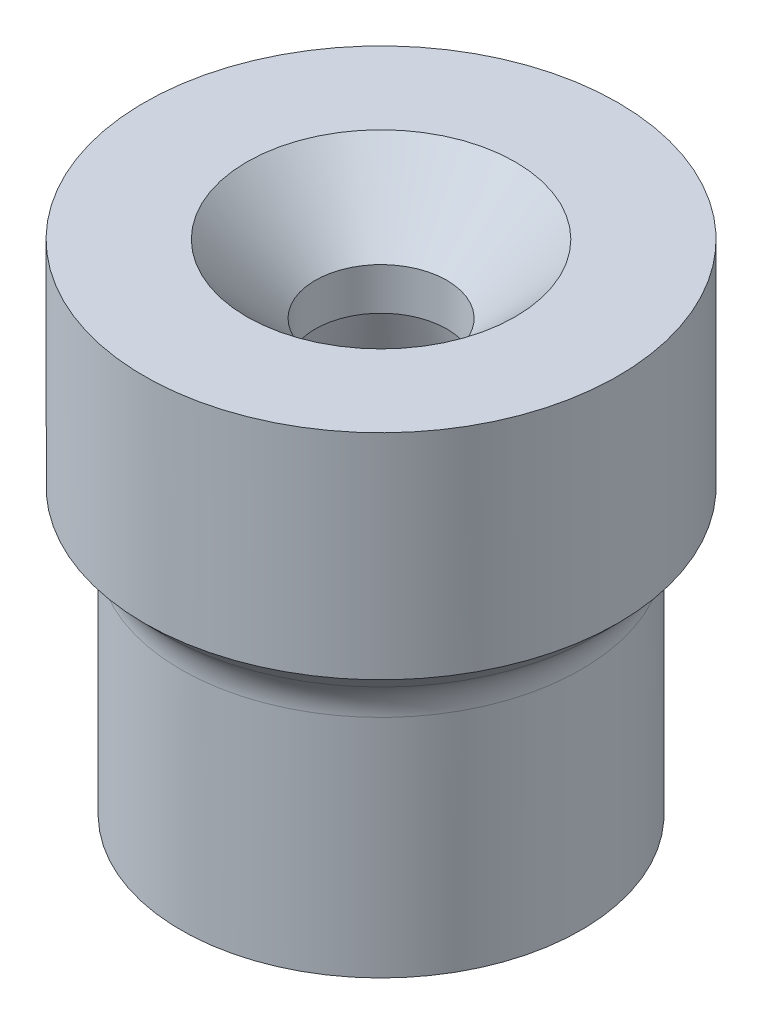
SolidWorks part; units mm, degrees
material "C (Grafite)"
ref_plane "Piano frontale" through (0, 0, 0) normal (0, 0, 1) x (1, 0, 0)
ref_plane "Piano superiore" through (0, 0, 0) normal (0, 1, 0) x (1, 0, 0)
ref_plane "Piano destro" through (0, 0, 0) normal (1, 0, 0) x (0, 0, -1)
sketch "Schizzo1" plane through (0, 0, 0) normal (0, 0, 1) x (1, 0, 0)
  line L0 (0, 0) -> (0, 63.7736) construction
  line L1 (-32.2345, 0) -> (-12.5, 73.6501)
  line L2 (-12.5, 73.6501) -> (-12.5, 81.6501)
  line L3 (-12.5, 81.6501) -> (-25.4904, 94.6405)
  line L4 (-25.4904, 94.6405) -> (-63, 94.6405)
  line L15 (-38, 64.6405) -> (-38, 0)
  line L16 (-38, 0) -> (-32.2345, 0)
  line L17 (-38, 64.6405) -> (-63, 94.6405)
  dimension "D1" = 25
  dimension "D2" = 64.469
  dimension "D6" = 76
  dimension "D9" = 8
  dimension "D3" = 15
  dimension "D4" = 94.6405
  dimension "D10" = 45
  dimension "D5" = 126
  dimension "D7" = 30
revolve "Rivoluzione1" add sketch "Schizzo1" angle 360 about L0
sketch "Schizzo4" plane through (0, 0, 0) normal (0, 0, 1) x (1, 0, 0)
  line L0 (-38, 64.6405) -> (-38, 94.6405)
  line L1 (-25.4904, 94.6405) -> (-63, 94.6405) construction
  line L2 (-38, 94.6405) -> (-63, 94.6405)
  line L3 (-63, 94.6405) -> (-63, 64.6405)
  line L4 (-63, 64.6405) -> (-38, 64.6405)
  line L5 (-38, 64.6405) -> (-38, 0) construction
revolve "Taglia-Rivoluzione3" cut sketch "Schizzo4" angle 360 about L0
sketch "Schizzo5" plane through (0, 0, 0) normal (0, 0, 1) x (1, 0, 0)
  line L0 (-38, 94.6405) -> (-45, 94.6405)
  line L1 (-38, 64.6405) -> (-38, 0) construction
  line L2 (-45, 94.6405) -> (-45, 54)
  line L3 (-45, 54) -> (-38, 54)
  line L4 (-25.4904, 94.6405) -> (-63, 94.6405) construction
  line L5 (0, 0) -> (0, 63.7736) construction
  line L6 (-38, 0) -> (-32.2345, 0) construction
  line L7 (-38, 54) -> (-38, 94.6405)
  line L9 (-45, 54) -> (-38, 47)
  line L10 (-38, 94.6405) -> (-38, 0) construction
  line L12 (-38, 54) -> (-38, 47)
  dimension "D1" = 7
  dimension "D2" = 90
  dimension "D3" = 54
revolve "Rivoluzione2" add sketch "Schizzo5" angle 360 about L5
fillet "Raccordo1" radius 10 1 edges at (0, 47, 38)
fillet "Raccordo2" [suppressed] radius 10
equation "\"epsilon\"= 6.65"
equation "\"D2@Schizzo1\"= sqr ( \"epsilon\" ) * \"D1@Schizzo1\""
